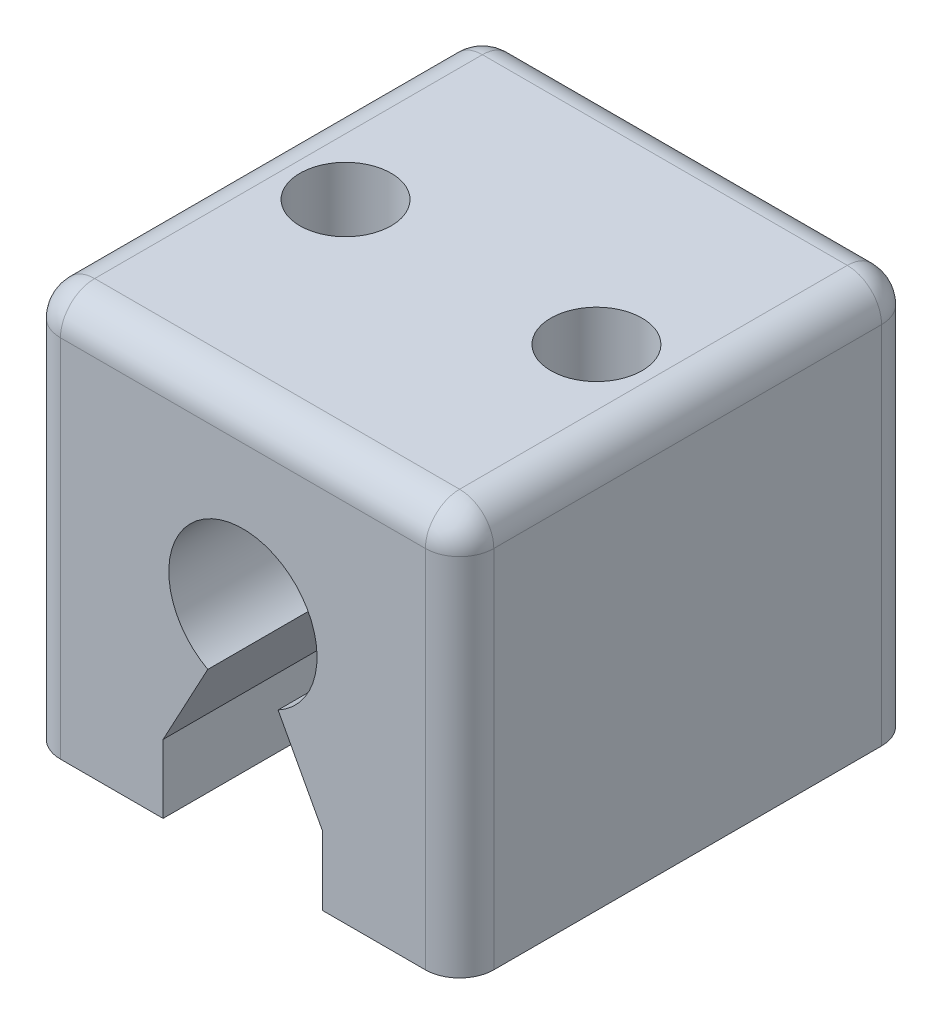
SolidWorks part; units mm, degrees
ref_plane "Front Plane" through (0, 0, 0) normal (0, 0, 1) x (1, 0, 0)
ref_plane "Top Plane" through (0, 0, 0) normal (0, 1, 0) x (1, 0, 0)
ref_plane "Right Plane" through (0, 0, 0) normal (1, 0, 0) x (0, 0, -1)
sketch "Sketch1" plane through (0, 0, 0) normal (0, 0, 1) x (1, 0, 0)
  line L0 (-15.7702, -12.0535) -> (14.2298, -12.0535)
  line L1 (14.2298, -12.0535) -> (14.2298, -8.0535)
  line L2 (-15.7702, -8.0535) -> (-15.7702, -12.0535)
  line L3 (-15.7702, -8.0535) -> (-7.7702, -8.0535)
  line L4 (6.2298, -8.0535) -> (6.2298, -2.0535)
  line L5 (6.2298, -8.0535) -> (14.2298, -8.0535)
  line L8 (-7.7702, -8.0535) -> (-7.7702, -2.0535)
  line L9 (-7.7702, -2.0535) -> (-3.8518, 5.2235)
  line L10 (6.2298, -2.0535) -> (2.3115, 5.2235)
  arc A1 (2.3115, 5.2235) -> (-3.8518, 5.2235) centre (-0.7702, 10.9465) ccw
  point P3 (-0.7702, -12.0535)
  dimension "D8" = 13
  dimension "D1" = 4
  dimension "D2" = 8
  dimension "D3" = 6
  dimension "D4" = 8
  dimension "D5" = 6
extrude "Boss-Extrude1" add sketch "Sketch1" along normal blind 40 contours L4 L10 A1 L9 L8 L3 L2 L0 L1 L5
shell "Shell1" thickness 4
sketch "Sketch2" plane through (0, 0, 40) normal (0, 0, 1) x (1, 0, 0)
  line L0 (18.2298, -16.0535) -> (18.2298, -4.0535) construction
  line L1 (-19.7702, -16.0535) -> (18.2298, -16.0535)
  line L2 (-19.7702, -16.0535) -> (-19.7702, -8.0535)
  line L3 (-19.7702, -8.0535) -> (18.2298, -8.0535)
  line L4 (18.2298, -16.0535) -> (18.2298, -8.0535)
  dimension "D1" = 8
extrude "Cut-Extrude1" cut sketch "Sketch2" against normal through all
sketch "Sketch3" plane through (0, 0, 40) normal (0, 0, 1) x (1, 0, 0)
  line L0 (-19.7702, 26.9465) -> (18.2298, 26.9465)
  line L1 (-7.7702, -8.0535) -> (-19.7702, -8.0535)
  line L4 (-19.7702, -8.0535) -> (-19.7702, 26.9465)
  line L5 (18.2298, -8.0535) -> (6.2298, -8.0535)
  line L6 (18.2298, -8.0535) -> (18.2298, 26.9465)
  line L8 (6.2298, -8.0535) -> (6.2298, 17.5119)
  line L13 (-7.7702, 17.5119) -> (-7.7702, -8.0535)
  line L14 (-7.7702, 17.5119) -> (6.2298, 17.5119)
  dimension "D1" = 35
  dimension "D2" = 35
extrude "Boss-Extrude2" add sketch "Sketch3" against normal through all contours L4 L0 L6 L5 L8 L14 L13 L1
sketch "Sketch4" plane through (0, -8.0535, 0) normal (0, -1, 0) x (1, 0, 0)
  line L1 (-19.7702, 0) -> (-19.7702, 40) construction
  circle A0 centre (-11.7702, 20) radius 2.1
  dimension "D1" = 4.2
  dimension "D2" = 8
extrude "Cut-Extrude2" cut sketch "Sketch4" against normal through all
sketch "Sketch5" plane through (0, 26.9465, 0) normal (0, 1, 0) x (1, 0, 0)
  circle A0 centre (-11.7702, -20) radius 4
  dimension "D1" = 8
extrude "Cut-Extrude4" cut sketch "Sketch5" against normal blind 28 contours A0
pattern_linear "LPattern1" count 2 spacing 22 along (1, 0, 0) of "Cut-Extrude2", "Cut-Extrude4"
fillet "Fillet1" radius 3 8 edges at (18.2298, 9.4465, 40) (18.2298, 9.4465, 0) (-19.7702, 9.4465, 0) (-19.7702, 9.4465, 40) (-19.7702, 26.9465, 20) (-0.7702, 26.9465, 40) (-0.7702, 26.9465, 0) (18.2298, 26.9465, 20)
